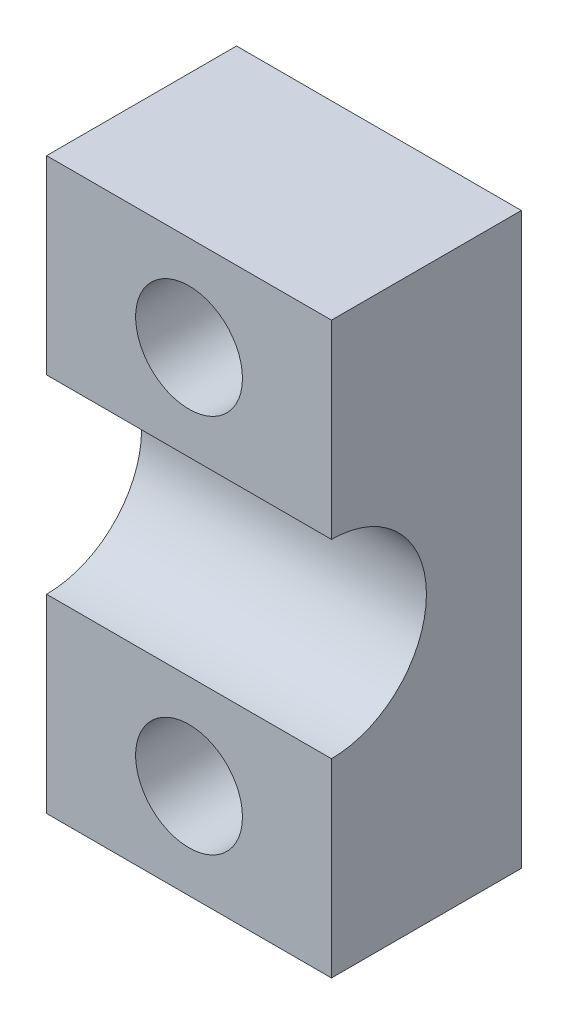
SolidWorks part; units mm, degrees
material "Printed PLA"
ref_plane "Front Plane" through (0, 0, 0) normal (0, 0, 1) x (1, 0, 0)
ref_plane "Top Plane" through (0, 0, 0) normal (0, 1, 0) x (1, 0, 0)
ref_plane "Right Plane" through (0, 0, 0) normal (1, 0, 0) x (0, 0, -1)
sketch "Sketch1" plane through (0, 0, 0) normal (1, 0, 0) x (0, 0, -1)
  line L0 (0, 4) -> (0, 12)
  line L1 (0, 12) -> (8, 12)
  line L2 (8, 12) -> (8, -12)
  line L3 (8, -12) -> (0, -12)
  line L4 (0, -12) -> (0, -4)
  line L5 (0, 4) -> (0, -4) construction
  arc A0 (0, -4) -> (0, 4) centre (0, 0) ccw
  dimension "D1" = 4
  dimension "D2" = 12
  dimension "D3" = 8
extrude "Boss-Extrude1" add sketch "Sketch1" along normal mid plane 12
sketch "Sketch2" plane through (0, 0, 0) normal (0, 0, 1) x (1, 0, 0)
  line L0 (0, -8) -> (0, 8) construction
  circle A0 centre (0, 8) radius 2.25
  circle A1 centre (0, -8) radius 2.25
  dimension "D1" = 4.5
  dimension "D2" = 16
extrude "Cut-Extrude1" cut sketch "Sketch2" against normal through all
